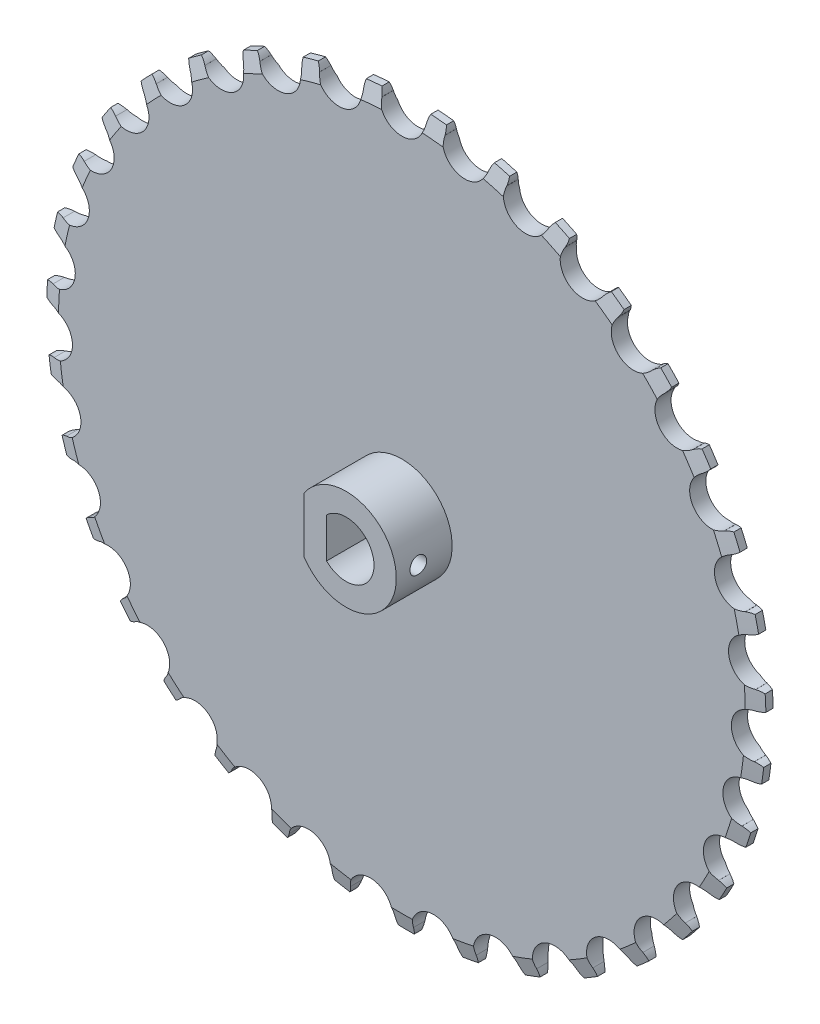
SolidWorks part; units mm, degrees
ref_plane "Front Plane" through (0, 0, 0) normal (0, 0, 1) x (1, 0, 0)
ref_plane "Top Plane" through (0, 0, 0) normal (0, 1, 0) x (1, 0, 0)
ref_plane "Right Plane" through (0, 0, 0) normal (1, 0, 0) x (0, 0, -1)
sketch "Sketch3" plane through (0, 0, 0) normal (1, 0, 0) x (0, 0, -1)
  line L0 (-59.9985, 0) -> (64.9862, 0) construction
  line L1 (-21.78, 0) -> (-18.88, 0)
  line L2 (-18.88, 0) -> (-18.88, 61.5)
  line L4 (-21.78, 0) -> (-21.78, 61.5)
  line L5 (-21.78, 61.5) -> (-20.98, 64.4017)
  line L6 (-20.98, 64.4017) -> (-19.68, 64.4017)
  line L7 (-19.68, 64.4017) -> (-18.88, 61.5)
  dimension "D1" = 3.01
  dimension "D2" = 2.9
  dimension "D3" = 3.01
  dimension "D4" = 1.3
  dimension "D5" = 61.5
revolve "Revolve1" add sketch "Sketch3" angle 360 about L0
sketch "Sketch7" plane through (0, 0, 21.78) normal (0, 0, 1) x (1, 0, 0)
  line L0 (-3.4982, 3.5725) -> (-3.4982, -3.5725)
  arc A0 (-3.4982, -3.5725) -> (-3.4982, 3.5725) centre (0, 0) ccw
  dimension "D1" = 10
extrude "Extrude-Thin1" add sketch "Sketch7" along normal blind 10 thin
sketch "Sketch11" plane through (0, 0, 0) normal (1, 0, 0) x (0, 0, -1)
  circle A0 centre (-27.8313, 0) radius 1.5
  dimension "D1" = 3
extrude "Cut-Extrude5" cut sketch "Sketch11" along normal through all
sketch "Sketch14" plane through (0, 0, 0) normal (0, 0, 1) x (1, 0, 0)
  arc A1 (-3.998, 62.9389) -> (3.998, 62.9389) centre (0, 63.0657) ccw
  arc A3 (4.011, 62.938) -> (3.998, 62.9389) centre (0, 0) ccw
  arc A4 (-4.011, 62.938) -> (-4.3702, 64.2533) centre (-7.9928, 62.5572) ccw
  arc A5 (4.3702, 64.2533) -> (4.011, 62.938) centre (7.9928, 62.5572) ccw
  arc A6 (-3.998, 62.9389) -> (-4.011, 62.938) centre (0, 0) ccw
  point P7 (7.9928, 62.5572)
extrude "Cut-Extrude15" cut sketch "Sketch14" along normal through all flip side to cut
pattern_circular "CirPattern2" count 35 over 360 about axis through (0, 0, 19.68) along (0, 0, 1) of "Cut-Extrude15"
sketch "Sketch17" plane through (0, 0, 21.78) normal (0, 0, 1) x (1, 0, 0)
  line L0 (-3.4982, 3.5725) -> (-3.4982, -3.5725)
  arc A0 (-3.4982, -3.5725) -> (-3.4982, 3.5725) centre (0, 0) ccw
extrude "Cut-Extrude16" cut sketch "Sketch17" against normal through all
